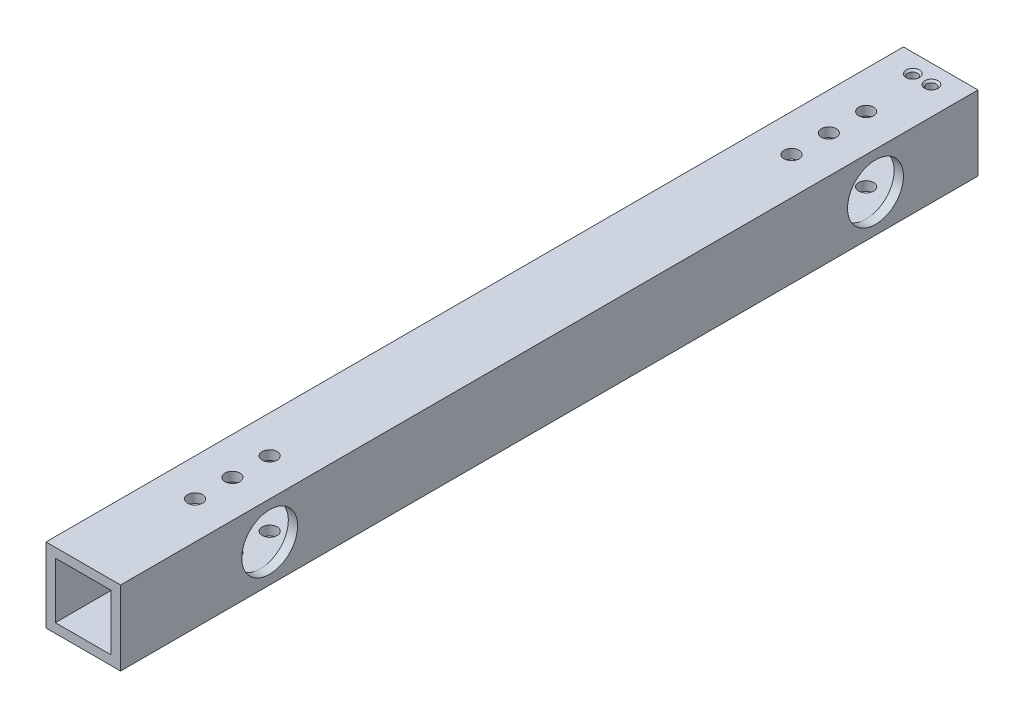
SolidWorks part; units mm, degrees
material "6061 Alloy"
ref_plane "Front" through (0, 0, 0) normal (0, 0, 1) x (1, 0, 0)
ref_plane "Top" through (0, 0, 0) normal (0, 1, 0) x (1, 0, 0)
ref_plane "Right" through (0, 0, 0) normal (1, 0, 0) x (0, 0, -1)
sketch "Sketch1" plane through (0, 0, 0) normal (0, 0, 1) x (1, 0, 0)
  line L1 (0, 0) -> (-25.4, 0)
  line L2 (0, 0) -> (0, 25.4)
  line L3 (0, 25.4) -> (-25.4, 25.4)
  line L4 (-25.4, 0) -> (-25.4, 25.4)
  line L5 (-3.175, 3.175) -> (-22.225, 3.175)
  line L6 (-3.175, 3.175) -> (-3.175, 22.225)
  line L7 (-3.175, 22.225) -> (-22.225, 22.225)
  line L8 (-22.225, 3.175) -> (-22.225, 22.225)
  dimension "D1" = 3.175
  dimension "D2" = 3.175
  dimension "D3" = 3.175
  dimension "D4" = 3.175
  dimension "D5" = 25.4
  dimension "D6" = 25.4
extrude "Boss-Extrude1" add sketch "Sketch1" along normal blind 292.1
hole_wizard "#10 Clearance Hole1" positions "Sketch2" profile "Sketch3" hole size "#10" standard "ANSI Inch"
sketch "Sketch2" plane through (0, 25.4, 0) normal (0, 1, 0) x (1, 0, 0)
  line L0 (0, -292.1) -> (-25.4, -292.1) construction
  line L1 (0, -292.1) -> (0, 0) construction
  point P0 (-12.7, -254)
  point P2 (-12.7, -241.3)
  point P4 (-12.7, -228.6)
  dimension "D1" = 12.7
  dimension "D2" = 12.7
  dimension "D3" = 38.1
  dimension "D4" = 12.7
sketch "Sketch3" plane through (-12.7, 25.4, 254) normal (1, 0, 0) x (0, 0, 1)
  line L0 (0, 0) -> (0, 26.9328)
  line L1 (0, 26.9328) -> (2.5527, 25.399)
  line L2 (2.5527, 25.399) -> (2.5527, 0)
  line L5 (2.5527, 0) -> (0, 0)
  line L10 (0, 26.9328) -> (-2.5527, 25.399) construction
  line L11 (0, -6.35) -> (0, 107.95) construction
  dimension "Hole Dia." = 5.1054
  dimension "Hole Depth" = 25.399
  dimension "Drill Angle" = 118
sketch "Sketch6" plane through (-25.4, 0, 0) normal (-1, 0, 0) x (0, 0, 1)
  line L0 (292.1, 25.4) -> (292.1, 0) construction
  line L1 (292.1, 0) -> (0, 0) construction
  line L2 (292.1, 25.4) -> (0, 25.4) construction
  line L3 (0, 25.4) -> (0, 0) construction
  circle A0 centre (241.3, 12.711) radius 9.525
  circle A1 centre (34.925, 12.711) radius 9.525
  dimension "D1" = 19.05
  dimension "D4" = 19.05
  dimension "D6" = 34.925
  dimension "D2" = 50.8
  dimension "D3" = 12.711
  dimension "D5" = 12.689
extrude "Cut-Extrude1" cut sketch "Sketch6" against normal up to surface and the other way through all up to face at (0, 12.7, 146.05)
hole_wizard "#4 Clearance Hole1" positions "Sketch7" profile "Sketch8" hole size "#4" standard "ANSI Inch"
sketch "Sketch7" plane through (0, 25.4, 0) normal (0, 1, 0) x (1, 0, 0)
  line L0 (0, 0) -> (-25.4, 0) construction
  line L2 (-25.4, -292.1) -> (-25.4, 0) construction
  point P0 (-9.525, -6.35)
  point P2 (-15.875, -6.35)
  dimension "D1" = 6.35
  dimension "D2" = 6.35
  dimension "D3" = 9.525
sketch "Sketch8" plane through (-9.525, 25.4, 6.35) normal (1, 0, 0) x (0, 0, 1)
  line L0 (0, 0) -> (0, 26.3796)
  line L1 (0, 26.3796) -> (1.6319, 25.399)
  line L2 (1.6319, 25.399) -> (1.6319, 0.635)
  line L3 (1.6319, 0.635) -> (2.267, 0)
  line L5 (2.267, 0) -> (0, 0)
  line L6 (-1.6319, 0.635) -> (-2.267, 0) construction
  line L10 (0, 26.3796) -> (-1.632, 25.399) construction
  line L11 (0, -6.35) -> (0, 107.95) construction
  dimension "Hole Dia." = 3.2639
  dimension "Hole Depth" = 25.399
  dimension "Near C'Sink Dia." = 4.5339
  dimension "Near C'Sink Angle" = 90
  dimension "Drill Angle" = 118
hole_wizard "#10 Clearance Hole2" positions "Sketch9" profile "Sketch10" hole size "#10" standard "ANSI Inch"
sketch "Sketch9" plane through (0, 25.4, 0) normal (0, 1, 0) x (1, 0, 0)
  line L1 (0, 0) -> (-25.4, 0) construction
  line L2 (0, -292.1) -> (0, 0) construction
  point P0 (-12.7, -50.8)
  point P2 (-12.7, -38.1)
  point P4 (-12.7, -25.4)
  dimension "D1" = 12.7
  dimension "D2" = 12.7
  dimension "D3" = 25.4
  dimension "D4" = 12.7
sketch "Sketch10" plane through (-12.7, 25.4, 50.8) normal (1, 0, 0) x (0, 0, 1)
  line L0 (0, 0) -> (0, 26.9328)
  line L1 (0, 26.9328) -> (2.5527, 25.399)
  line L2 (2.5527, 25.399) -> (2.5527, 0)
  line L5 (2.5527, 0) -> (0, 0)
  line L10 (0, 26.9328) -> (-2.5527, 25.399) construction
  line L11 (0, -6.35) -> (0, 107.95) construction
  dimension "Hole Dia." = 5.1054
  dimension "Hole Depth" = 25.399
  dimension "Drill Angle" = 118
